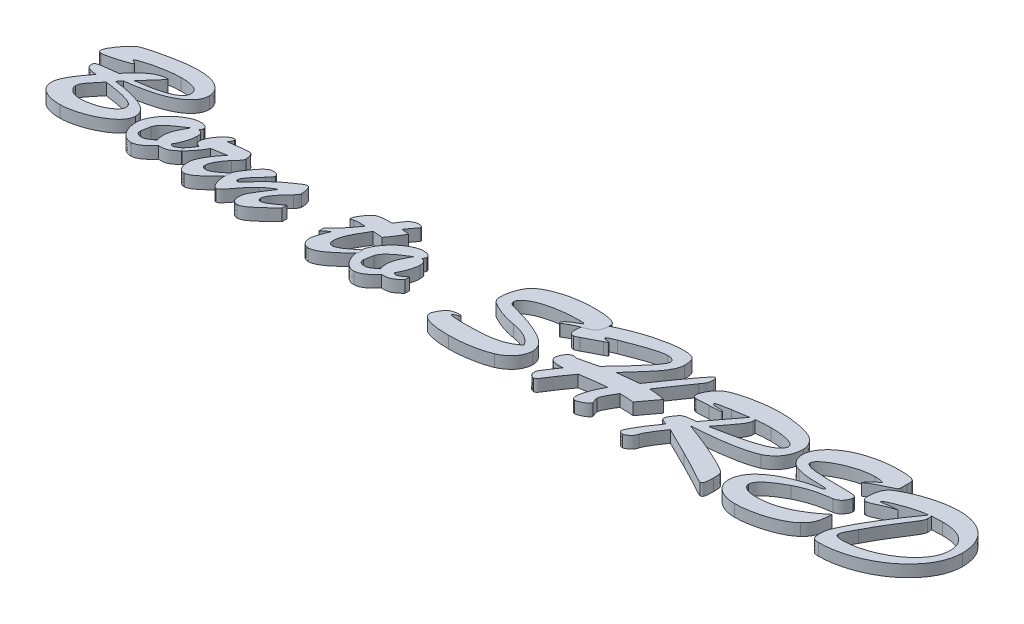
SolidWorks part; units mm, degrees
ref_plane "Front Plane" through (0, 0, 0) normal (0, 0, 1) x (1, 0, 0)
ref_plane "Top Plane" through (0, 0, 0) normal (0, 1, 0) x (1, 0, 0)
ref_plane "Right Plane" through (0, 0, 0) normal (1, 0, 0) x (0, 0, -1)
sketch "Sketch1" plane through (0, 0, 0) normal (0, 1, 0) x (1, 0, 0)
  text T0 "Born to SHRED" font "Brush Script MT" height in points 100
  point P1 (0, 0)
  point P2 (21.9647, -6.9807)
extrude "Boss-Extrude1" add sketch "Sketch1" along normal blind 2.54
